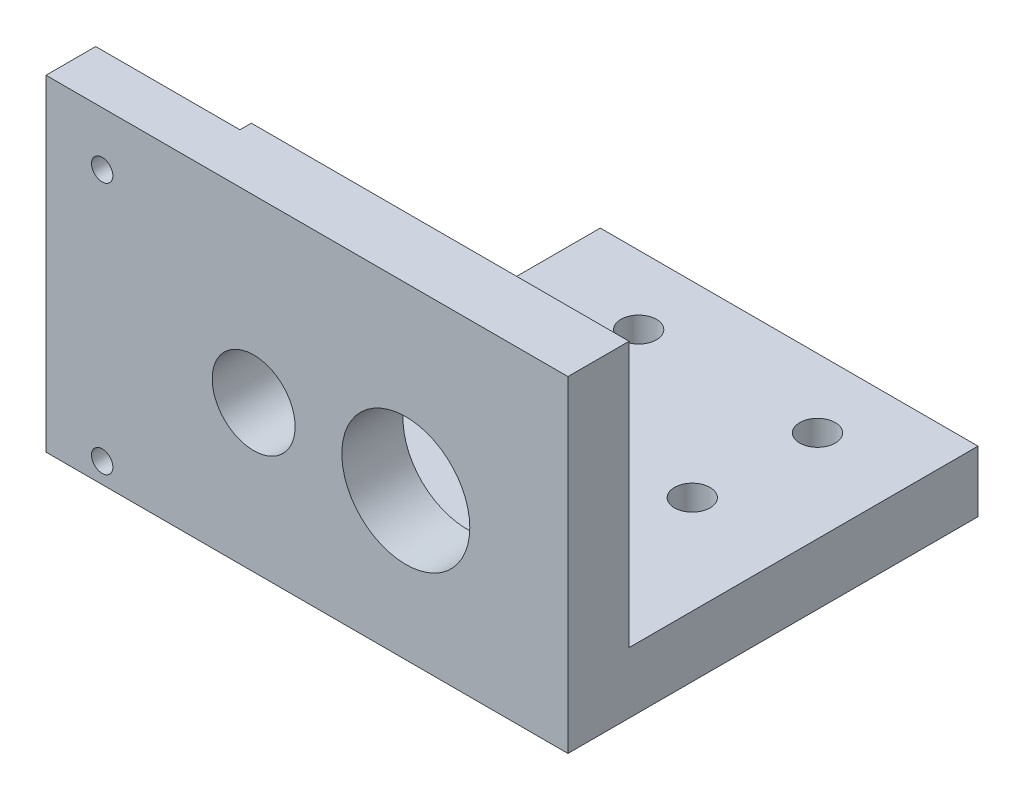
SolidWorks part; units mm, degrees
ref_plane "Front Plane" through (0, 0, 0) normal (0, 0, 1) x (1, 0, 0)
ref_plane "Top Plane" through (0, 0, 0) normal (0, 1, 0) x (1, 0, 0)
ref_plane "Right Plane" through (0, 0, 0) normal (1, 0, 0) x (0, 0, -1)
sketch "Sketch3" plane through (0, 0, 0) normal (1, 0, 0) x (0, 0, -1)
  line L0 (0, 0) -> (0, -26.129)
  line L1 (0, -26.129) -> (24.5342, -26.129)
extrude "Extrude-Thin1" add sketch "Sketch3" against normal blind 36.7 thin
sketch "Sketch4" plane through (0, 0, 0) normal (0, 1, 0) x (1, 0, 0)
  line L0 (0, 0) -> (0, 24.5342) construction
  line L1 (-47.6935, -0.8045) -> (-26.56, -0.8045)
  line L2 (-47.6935, -0.8045) -> (-47.6935, 39.2442)
  line L3 (-47.6935, 39.2442) -> (-26.56, 39.2442)
  line L4 (-26.56, -0.8045) -> (-26.56, 39.2442)
  point P6 (-45.0763, -0.9391)
  point P7 (0, 0)
  point P8 (-45.9184, 1.2963)
  point P9 (-47.6935, -0.8045)
  dimension "D1" = 26.56
extrude "Cut-Extrude2" cut sketch "Sketch4" against normal through all contours L2 L1 L4 L3
sketch "Sketch5" plane through (0, 0, 0) normal (0, 0, 1) x (1, 0, 0)
  line L0 (0, 0) -> (0, -26.129) construction
  line L1 (-26.56, -26.129) -> (0, -26.129) construction
  circle A0 centre (-11.4, -20.119) radius 4.5
  dimension "D1" = 9
  dimension "D2" = 11.4
  dimension "D3" = 6.01
extrude "Cut-Extrude3" cut sketch "Sketch5" along normal through all
sketch "Sketch6" plane through (0, 0, 0) normal (0, 0, 1) x (1, 0, 0)
  line L0 (0, 0) -> (0, -26.129) construction
  line L1 (-26.56, -26.129) -> (0, -26.129) construction
  circle A0 centre (-22.1, -20.119) radius 2.915
  dimension "D1" = 5.83
  dimension "D2" = 22.1
  dimension "D3" = 6.01
extrude "Cut-Extrude4" cut sketch "Sketch6" along normal through all
sketch "Sketch7" plane through (0, 0, 0) normal (0, 0, 1) x (1, 0, 0)
  line L0 (0, 0) -> (0, -26.129) construction
  line L1 (-26.56, -26.129) -> (0, -26.129) construction
  circle A0 centre (-32.75, -11.249) radius 0.75
  circle A1 centre (-32.75, -28.999) radius 0.75
  dimension "D1" = 1.5
  dimension "D2" = 1.5
  dimension "D5" = 17.75
  dimension "D3" = 32.75
  dimension "D4" = 32.75
  dimension "D6" = 14.88
extrude "Cut-Extrude5" cut sketch "Sketch7" along normal through all
sketch "Sketch8" plane through (0, 0, 0) normal (0, 1, 0) x (1, 0, 0)
  circle A0 centre (-19.0273, 11.3503) radius 1.25
  circle A1 centre (-19.0273, 19.7019) radius 1.25
  circle A2 centre (-6.9072, 11.3503) radius 1.25
  circle A3 centre (-6.4518, 19.7019) radius 1.25
  point P8 (-6.4659, 9.7833)
  point P9 (-5.3448, 18.8822)
  point P10 (-5.3448, 11.7735)
  point P11 (-6.8975, 10.9478)
  point P12 (-6.8975, 18.1611)
  point P13 (0, 0)
  point P14 (0, 0)
  point P15 (0, 0)
  point P16 (0, 0)
  point P17 (-19.5485, 11.3503)
  point P18 (-19.0273, 11.3503)
  point P19 (-19.0273, 19.7019)
  dimension "D1" = 2.5
  dimension "D2" = 2.5
  dimension "D3" = 2.5
  dimension "D4" = 2.5
extrude "Cut-Extrude6" cut sketch "Sketch8" against normal through all
sketch "Sketch9" plane through (0, 0, 0) normal (0, 0, 1) x (1, 0, 0)
  line L0 (0, 0) -> (0, -30.429) construction
  line L1 (-36.7, 0) -> (0, 0)
  line L2 (-36.7, 0) -> (-36.7, -7.4755)
  line L3 (-36.7, -7.4755) -> (0, -7.4755)
  line L4 (0, 0) -> (0, -7.4755)
extrude "Cut-Extrude7" cut sketch "Sketch9" along normal through all
